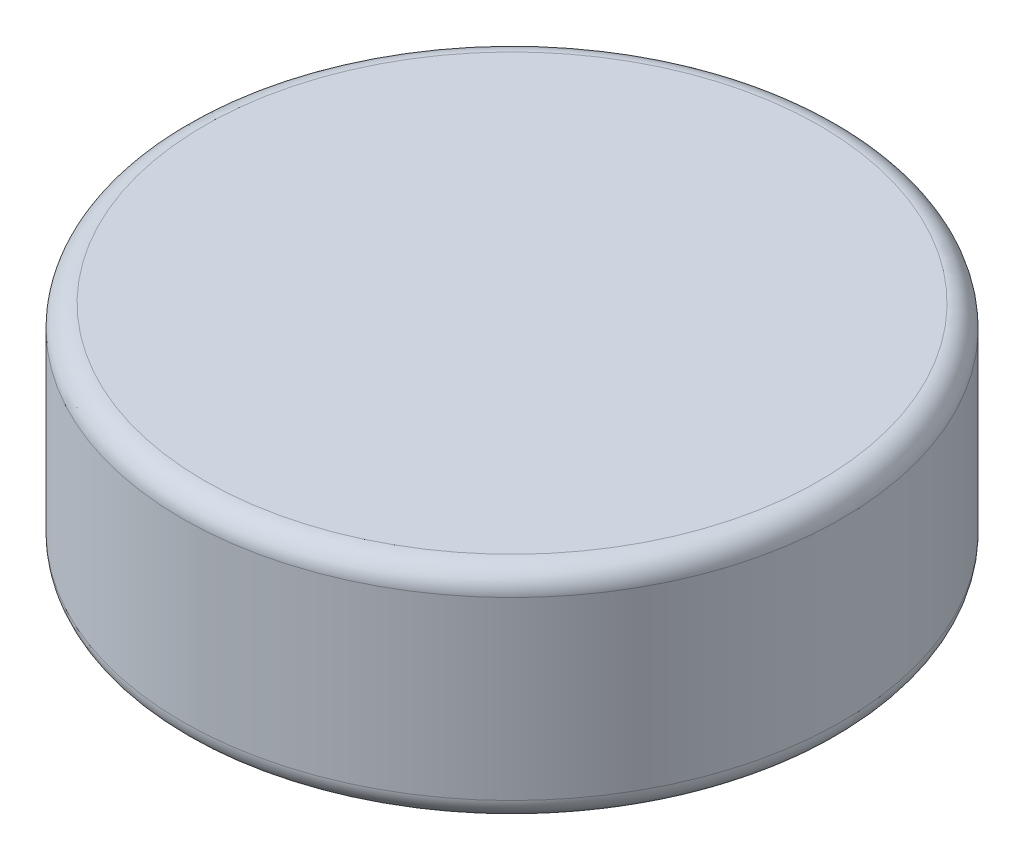
SolidWorks part; units mm, degrees
material "Natural Rubber"
ref_plane "Front Plane" through (0, 0, 0) normal (0, 0, 1) x (1, 0, 0)
ref_plane "Top Plane" through (0, 0, 0) normal (0, 1, 0) x (1, 0, 0)
ref_plane "Right Plane" through (0, 0, 0) normal (1, 0, 0) x (0, 0, -1)
sketch "Sketch1" plane through (0, 0, 0) normal (0, 1, 0) x (1, 0, 0)
  circle A0 centre (0, 0) radius 38.1
  dimension "D1" = 76.2
extrude "Boss-Extrude1" add sketch "Sketch1" along normal blind 25.4
fillet "Fillet1" radius 2.54 2 edges at (0, 0, 38.1) (0, 25.4, 38.1)
